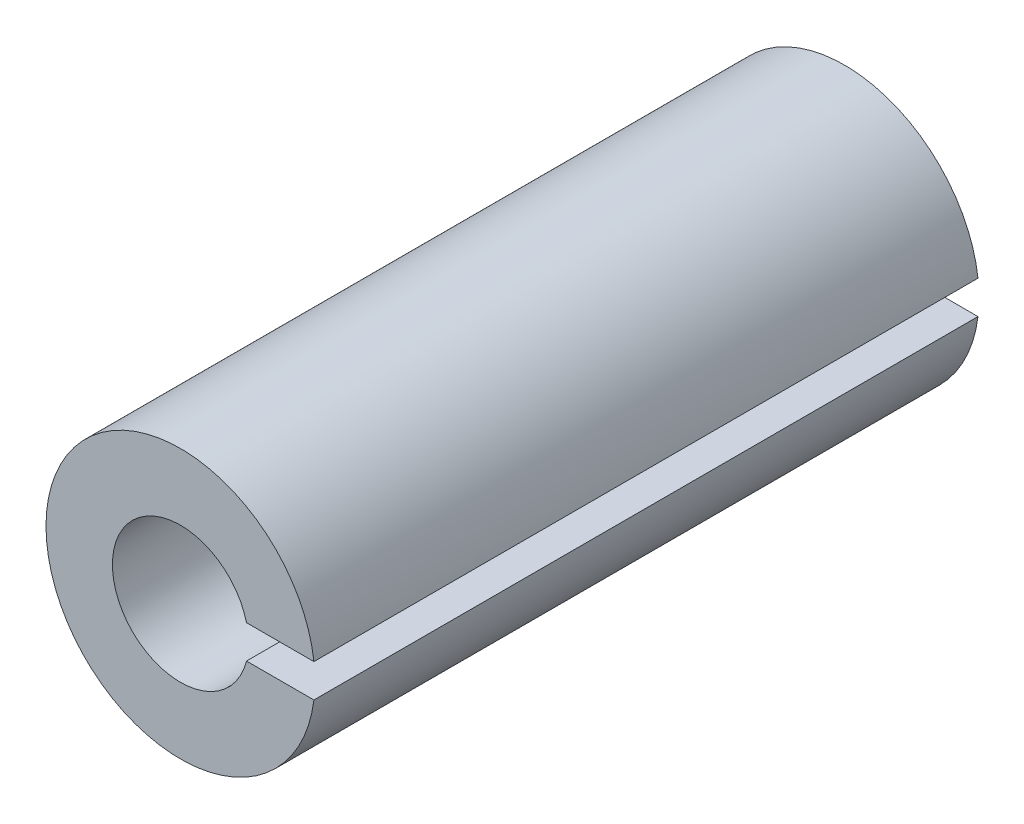
SolidWorks part; units mm, degrees
ref_plane "Front Plane" through (0, 0, 0) normal (0, 0, 1) x (1, 0, 0)
ref_plane "Top Plane" through (0, 0, 0) normal (0, 1, 0) x (1, 0, 0)
ref_plane "Right Plane" through (0, 0, 0) normal (1, 0, 0) x (0, 0, -1)
sketch "Sketch1" plane through (0, 0, 0) normal (0, 0, 1) x (1, 0, 0)
  circle A0 centre (0, 0) radius 4.05
  circle A1 centre (0, 0) radius 2.05
  dimension "D1" = 4.1
  dimension "D2" = 2
extrude "Boss-Extrude1" add sketch "Sketch1" along normal blind 20
sketch "Sketch2" plane through (0, 0, 20) normal (0, 0, 1) x (1, 0, 0)
  line L0 (0, 0) -> (7.7443, 0)
extrude "Cut-Extrude-Thin1" cut sketch "Sketch2" against normal blind 20 and the other way through all thin thin type mid plane wall 1
